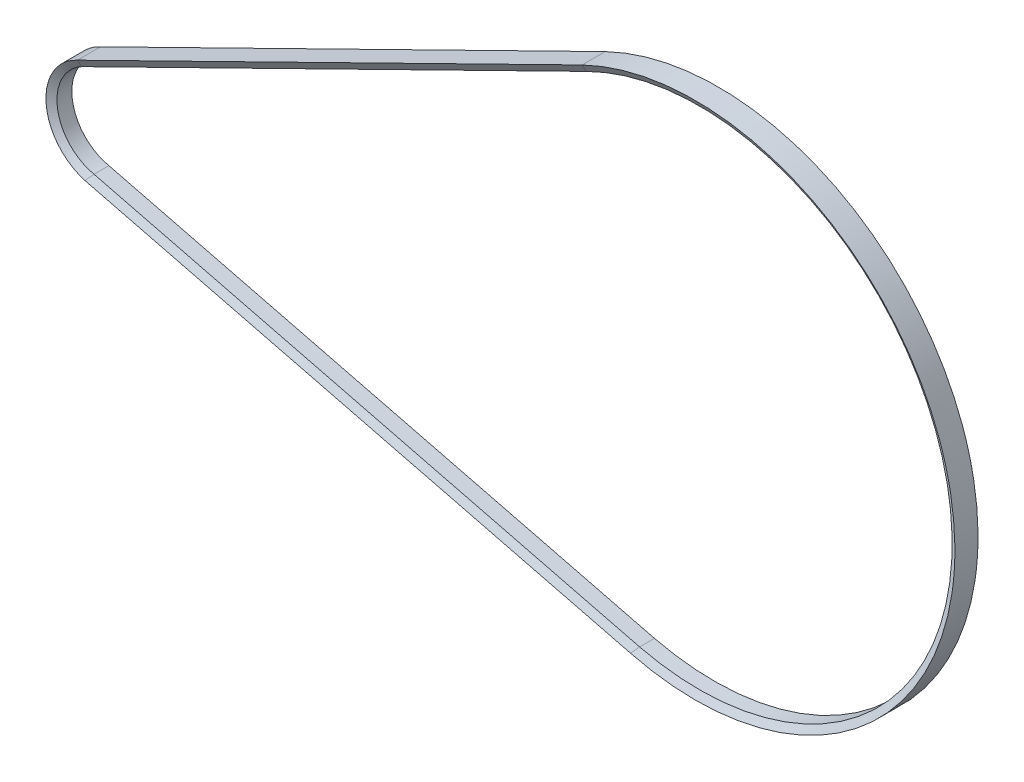
SolidWorks part; units mm, degrees
ref_plane "Alzado" through (0, 0, 0) normal (0, 0, 1) x (1, 0, 0)
ref_plane "Planta" through (0, 0, 0) normal (0, 1, 0) x (1, 0, 0)
ref_plane "Vista lateral" through (0, 0, 0) normal (1, 0, 0) x (0, 0, -1)
sketch "Croquis2" plane through (0, 0, 0) normal (0, 0, 1) x (1, 0, 0)
  line L0 (0, 0) -> (1, 0) construction
  line L1 (0, 0) -> (0, 1) construction
  line L2 (-37.6427, -150.3596) -> (-367.6531, -67.7411)
  line L3 (-373.6785, -11.0465) -> (-68.4049, 139.0891)
  arc A0 (-68.4049, 139.0891) -> (-37.6427, -150.3596) centre (0, 0) cw
  arc A1 (-367.6531, -67.7411) -> (-373.6785, -11.0465) centre (-360.28, -38.29) cw
ref_plane "Plano1" through (-68.4049, 0, 0) normal (1, 0, 0) x (0, 0, -1)
sketch "Croquis3" plane through (-68.4049, 0, 0) normal (1, 0, 0) x (0, 0, -1)
  line L9 (-4.5, 136.7691) -> (4.5, 136.7691)
  line L13 (-4.5, 136.7691) -> (-7, 141.4091)
  line L14 (-7, 141.4091) -> (7, 141.4091)
  line L15 (7, 141.4091) -> (4.5, 136.7691)
  dimension "D2" = 9
  dimension "D3" = 14
sweep "Barrer1" add profiles "Croquis3" path "Croquis2"
